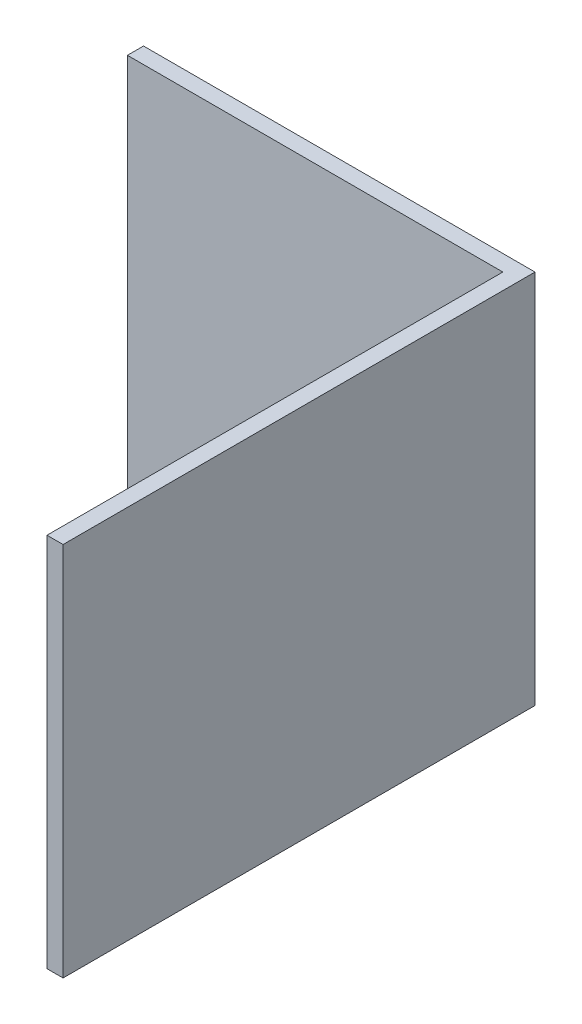
SolidWorks part; units mm, degrees
ref_plane "Front Plane" through (0, 0, 0) normal (0, 0, 1) x (1, 0, 0)
ref_plane "Top Plane" through (0, 0, 0) normal (0, 1, 0) x (1, 0, 0)
ref_plane "Right Plane" through (0, 0, 0) normal (1, 0, 0) x (0, 0, -1)
sketch "Sketch1" plane through (0, 0, 0) normal (0, 1, 0) x (1, 0, 0)
  line L0 (-57.9474, 6.4474) -> (12.0526, 6.4474)
  line L1 (12.0526, 6.4474) -> (12.0526, -78.5526)
  line L2 (12.0526, -78.5526) -> (15.0526, -78.5526)
  line L3 (15.0526, -78.5526) -> (15.0526, 9.4474)
  line L4 (15.0526, 9.4474) -> (-57.9474, 9.4474)
  line L5 (-57.9474, 9.4474) -> (-57.9474, 6.4474)
  dimension "D1" = 3
  dimension "D2" = 3
  dimension "D3" = 70
  dimension "D4" = 85
extrude "Boss-Extrude1" add sketch "Sketch1" along normal blind 70
